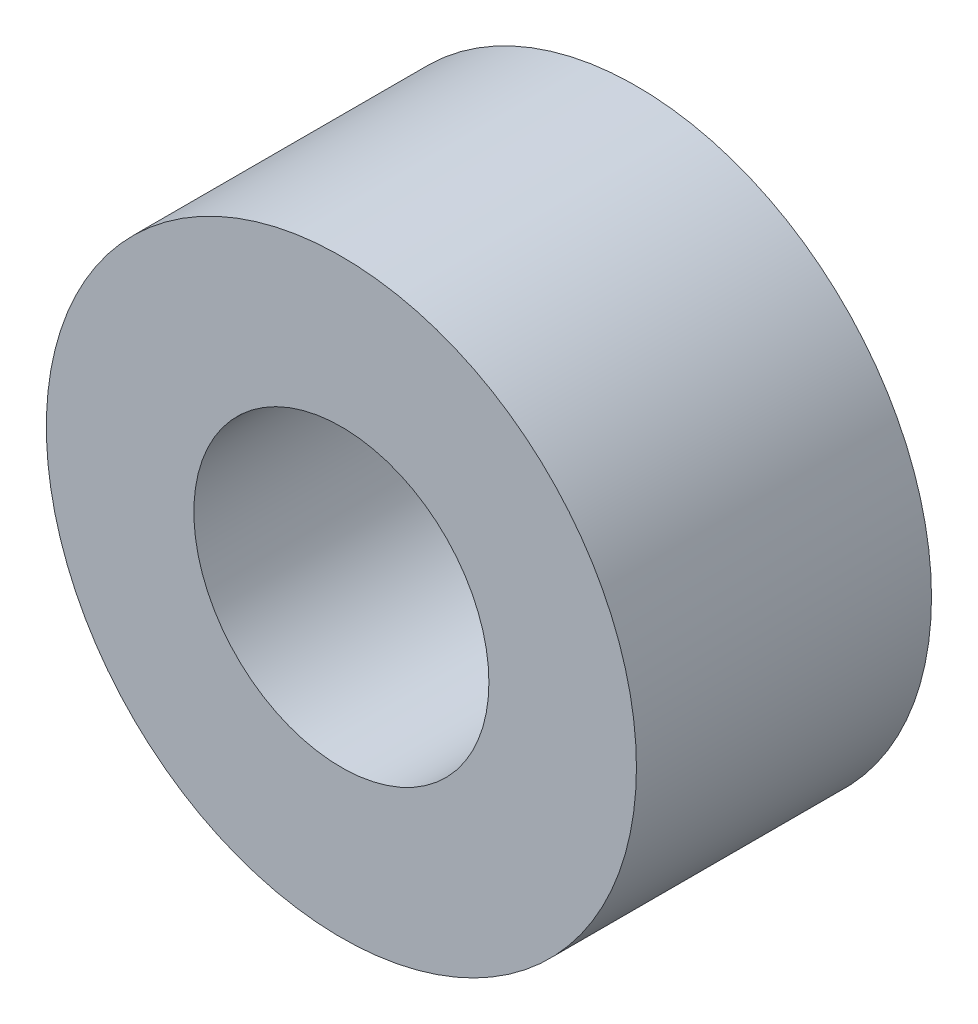
SolidWorks part; units mm, degrees
material "Alloy Steel"
ref_plane "Front Plane" through (0, 0, 0) normal (0, 0, 1) x (1, 0, 0)
ref_plane "Top Plane" through (0, 0, 0) normal (0, 1, 0) x (1, 0, 0)
ref_plane "Right Plane" through (0, 0, 0) normal (1, 0, 0) x (0, 0, -1)
sketch "Sketch1" plane through (0, 0, 0) normal (0, 0, 1) x (1, 0, 0)
  circle A0 centre (0, 0) radius 6
  circle A1 centre (0, 0) radius 3
  dimension "D1" = 12
  dimension "D2" = 6
extrude "Boss-Extrude1" add sketch "Sketch1" along normal blind 6
